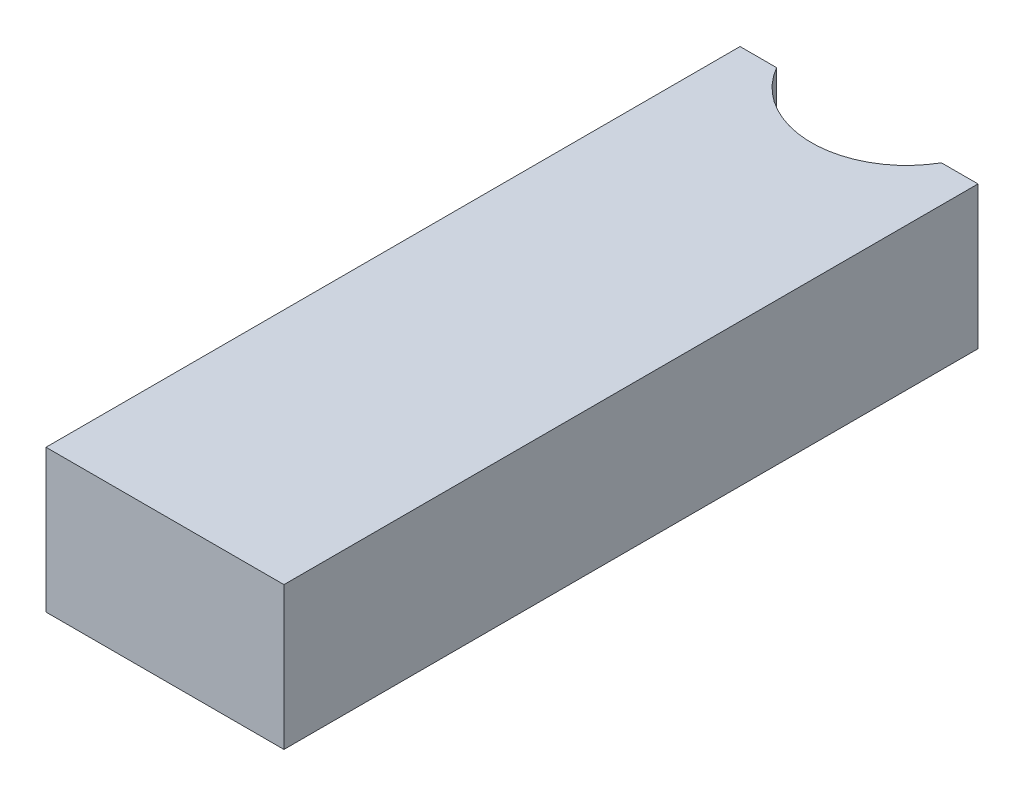
SolidWorks part; units mm, degrees
material "Custom Plastic"
ref_plane "X-Y Datum" through (0, 0, 0) normal (0, 0, 1) x (1, 0, 0)
ref_plane "X-Z Datum" through (0, 0, 0) normal (0, 1, 0) x (1, 0, 0)
ref_plane "Y-Z Datum" through (0, 0, 0) normal (1, 0, 0) x (0, 0, -1)
sketch "Sketch1" plane through (0, 0, 0) normal (0, 0, 1) x (1, 0, 0)
  line L1 (-15.875, 9.525) -> (15.875, 9.525)
  line L2 (-15.875, 9.525) -> (-15.875, -9.525)
  line L3 (-15.875, -9.525) -> (15.875, -9.525)
  line L4 (15.875, 9.525) -> (15.875, -9.525)
  line L5 (-15.875, 9.525) -> (15.875, -9.525) construction
  line L6 (-15.875, -9.525) -> (15.875, 9.525) construction
  point P0 (0, 0)
  dimension "D1" = 31.75
  dimension "D2" = 19.05
extrude "Boss-Extrude1" add sketch "Sketch1" along normal blind 92.6084
sketch "Sketch2" plane through (0, 9.525, 0) normal (0, 1, 0) x (1, 0, 0)
  circle A0 centre (0, 6.35) radius 12.7
  point P2 (0, -6.35)
  dimension "D1" = 25.4
  dimension "D2" = 6.35
extrude "Cut-Extrude1" cut sketch "Sketch2" against normal through all
